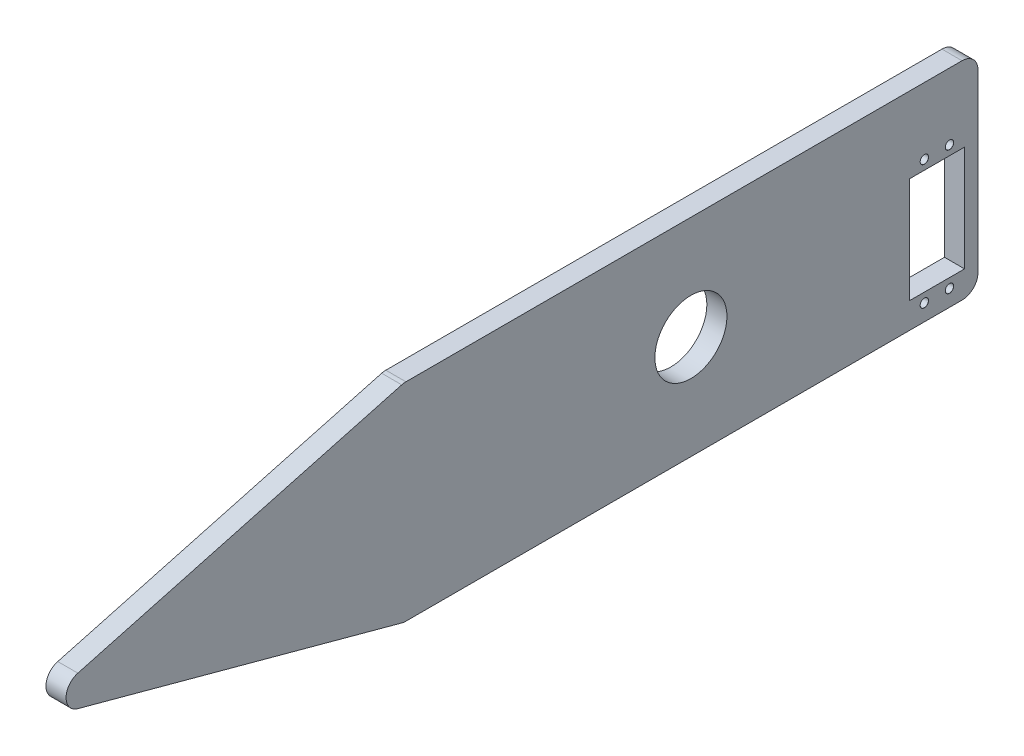
SolidWorks part; units mm, degrees
ref_plane "Front Plane" through (0, 0, 0) normal (1, 0, 0) x (0, 1, 0)
ref_plane "Top Plane" through (0, 0, 0) normal (0, 0, 1) x (0, 1, 0)
ref_plane "Right Plane" through (0, 0, 0) normal (0, 1, 0) x (-1, 0, 0)
sketch "Sketch1" plane through (0, 0, 0) normal (1, 0, 0) x (0, 1, 0)
  line L0 (-41.275, 114.3) -> (-41.275, -114.3)
  line L1 (-41.275, -114.3) -> (41.275, -114.3)
  line L2 (41.275, -114.3) -> (41.275, 114.3)
  line L3 (41.275, 114.3) -> (0, 266.7)
  line L4 (0, 266.7) -> (-41.275, 114.3)
  line L5 (0, 266.7) -> (0, 0) construction
  line L6 (-41.275, 114.3) -> (0, 114.3) construction
  line L7 (0, 114.3) -> (41.275, 114.3) construction
  circle A0 centre (0, 0) radius 6.35 construction
  circle A1 centre (0, 0) radius 14.351
  dimension "D5" = 12.7
  dimension "D6" = 28.702
  dimension "D1" = 228.6
  dimension "D2" = 381
  dimension "D3" = 114.3
  dimension "D4" = 82.55
sketch "Sketch2" plane through (0, 0, 0) normal (1, 0, 0) x (0, 1, 0)
  line L0 (-37.25, -97.95) -> (-30, -97.95) construction
  line L1 (-30, -87.95) -> (10, -87.95)
  line L2 (-30, -87.95) -> (-30, -107.95)
  line L3 (-30, -107.95) -> (10, -107.95)
  line L9 (-30, -88.95) -> (-37.25, -88.95)
  line L10 (-30, -88.95) -> (-30, -106.95)
  line L11 (-30, -106.95) -> (-37.25, -106.95)
  line L12 (-37.25, -88.95) -> (-37.25, -106.95)
  line L13 (10, -87.95) -> (10, -107.95)
  line L14 (-10, -87.95) -> (-10, -107.95) construction
  line L15 (10, -106.95) -> (17.25, -106.95)
  line L16 (17.25, -88.95) -> (17.25, -106.95)
  line L17 (10, -88.95) -> (17.25, -88.95)
  line L18 (-34.75, -88.95) -> (-34.75, -92.95) construction
  line L19 (-34.75, -92.95) -> (-34.75, -102.95) construction
  line L20 (-34.75, -102.95) -> (-34.75, -106.95) construction
  line L21 (14.75, -102.95) -> (14.75, -106.95) construction
  line L22 (14.75, -92.95) -> (14.75, -102.95) construction
  line L23 (14.75, -88.95) -> (14.75, -92.95) construction
  line L24 (0, -97.95) -> (10, -97.95) construction
  line L25 (0, 0) -> (0, -97.95) construction
  line L26 (-41.275, -114.3) -> (41.275, -114.3) construction
  circle A0 centre (0, -97.95) radius 3.9853
  circle A1 centre (-34.75, -92.95) radius 2.1
  dimension "D9" = 4.2
  dimension "D1" = 40
  dimension "D2" = 54.5
  dimension "D3" = 10
  dimension "D4" = 49.5
  dimension "D5" = 20
  dimension "D6" = 1
  dimension "D7" = 10
  dimension "D8" = 6.35
extrude "Boss-Extrude2" add sketch "Sketch1" along normal mid plane 8.001
fillet "Fillet1" radius 6.35 5 edges at (0, 41.275, -114.3) (0, -41.275, -114.3) (0, 0, 266.7) (0, -41.275, 114.3) (0, 41.275, 114.3)
hole_wizard "Tap Drill for M4x0.7 Tap1" positions "Sketch3" profile "Sketch4" hole size "M4x0.7" standard "ANSI Metric" end condition through all
sketch "Sketch3" plane through (4.0005, 0, 0) normal (1, 0, 0) x (0, 1, 0)
  point P0 (-34.75, -92.95)
  point P3 (-34.75, -102.95)
  point P6 (14.75, -92.95)
  point P9 (14.75, -102.95)
sketch "Sketch4" plane through (4.0005, -34.75, -92.95) normal (0, 1, 0) x (0, 0, -1)
  line L0 (0, 0) -> (0, 8.001)
  line L1 (0, 8.001) -> (1.65, 8.001)
  line L2 (1.65, 8.001) -> (1.65, 0.025)
  line L3 (1.65, 0.025) -> (1.675, 0)
  line L5 (1.675, 0) -> (0, 0)
  line L6 (-1.65, 0.025) -> (-1.675, 0) construction
  line L11 (0, -6.35) -> (0, 107.95) construction
  dimension "Thru Hole Dia." = 3.3
  dimension "Thru Hole Depth" = 8.001
  dimension "Near C'Sink Dia." = 3.35
  dimension "Near C'Sink Angle" = 90
sketch "Sketch5" plane through (4.0005, 0, 0) normal (1, 0, 0) x (0, 1, 0)
  line L8 (11, -108.95) -> (11, -86.95)
  line L9 (-31, -108.95) -> (11, -108.95)
  line L10 (-31, -86.95) -> (-31, -108.95)
  line L11 (11, -86.95) -> (-31, -86.95)
  line L12 (11, -108.95) -> (11, -86.95)
  line L13 (-31, -108.95) -> (11, -108.95)
  line L14 (-31, -86.95) -> (-31, -108.95)
  line L15 (11, -86.95) -> (-31, -86.95)
  dimension "D1" = 1
extrude "Cut-Extrude1" cut sketch "Sketch5" against normal through all
